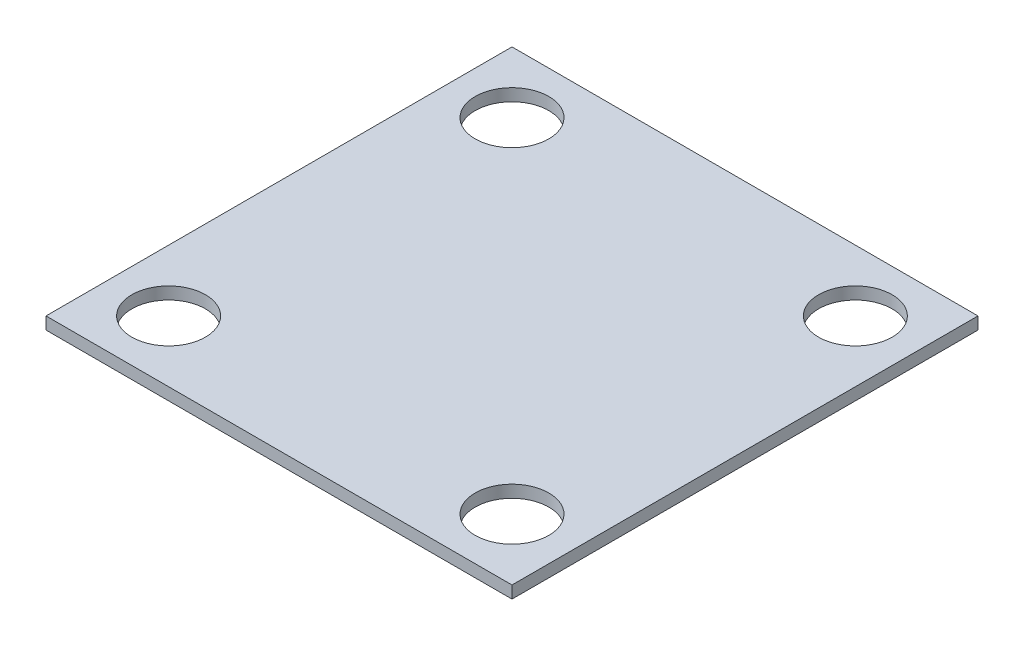
SolidWorks part; units mm, degrees
material "AISI 1035 Сталь (SS)"
ref_plane "Спереди (XY)" through (0, 0, 0) normal (0, 0, 1) x (1, 0, 0)
ref_plane "Сверху (XZ)" through (0, 0, 0) normal (0, 1, 0) x (1, 0, 0)
ref_plane "Справа (ZY)" through (0, 0, 0) normal (1, 0, 0) x (0, 0, -1)
sketch "Эскиз1" plane through (0, 0, 0) normal (0, 1, 0) x (1, 0, 0)
  line L1 (19, -19) -> (-19, -19)
  line L2 (19, -19) -> (19, 19)
  line L3 (19, 19) -> (-19, 19)
  line L4 (-19, -19) -> (-19, 19)
  line L5 (19, -19) -> (-19, 19) construction
  line L6 (19, 19) -> (-19, -19) construction
  circle A0 centre (-14, 14) radius 3
  circle A1 centre (14, 14) radius 3
  circle A2 centre (14, -14) radius 3
  circle A3 centre (-14, -14) radius 3
  point P0 (0, 0)
  point P8 (-19, 0)
  point P18 (0, 0)
  point P27 (0, 0)
  dimension "D3" = 6
  dimension "D1" = 38
  dimension "D2" = 38
  dimension "D4" = 14
  dimension "D5" = 4
extrude "Бобышка-Вытянуть1" add sketch "Эскиз1" along normal blind 1
